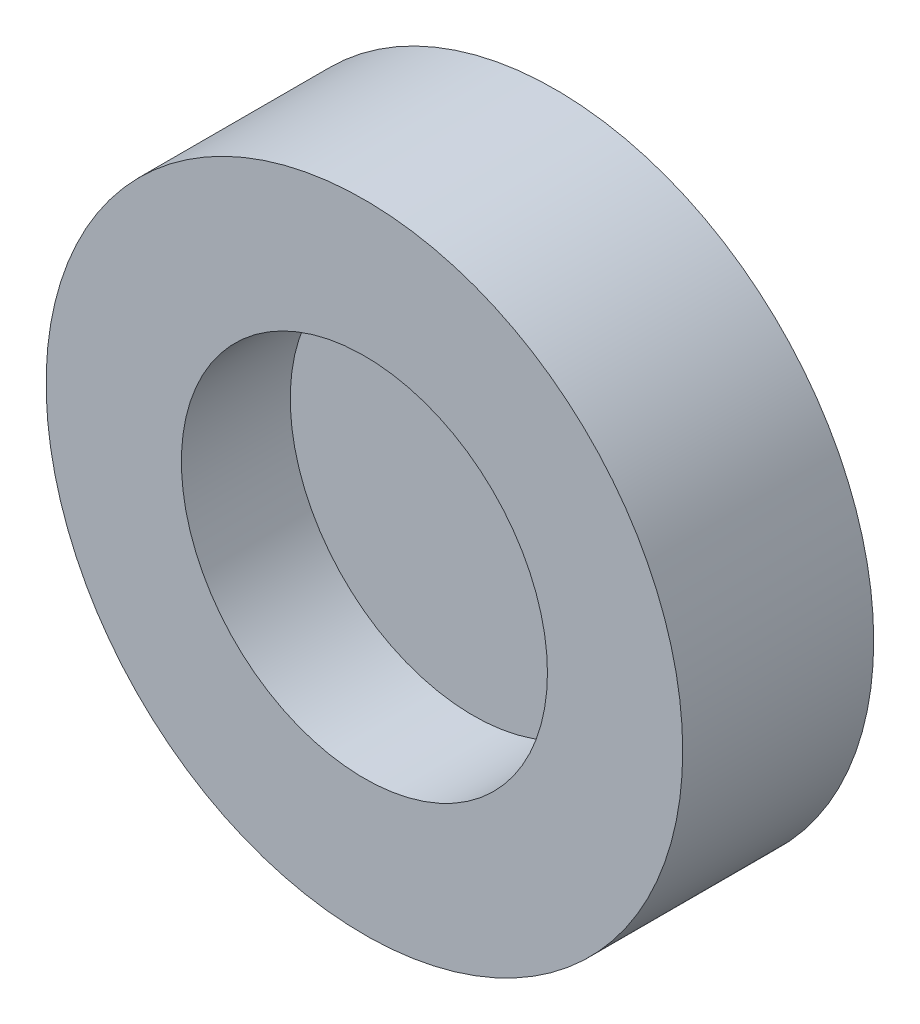
SolidWorks part; units mm, degrees
ref_plane "前视基准面" through (0, 0, 0) normal (0, 0, 1) x (1, 0, 0)
ref_plane "上视基准面" through (0, 0, 0) normal (0, 1, 0) x (1, 0, 0)
ref_plane "右视基准面" through (0, 0, 0) normal (1, 0, 0) x (0, 0, -1)
other "Configuration Table"
sketch "草图1" plane through (0, 0, 0) normal (0, 0, 1) x (1, 0, 0)
  circle A0 centre (-113.7233, 27.9708) radius 10
extrude "凸台-拉伸1" add sketch "草图1" against normal blind 6 from surface at -13.4389
sketch "草图2" plane through (0, 0, -13.4389) normal (0, 0, 1) x (1, 0, 0)
  circle A0 centre (-113.7233, 27.9708) radius 5.75
extrude "切除-拉伸1" cut sketch "草图2" against normal blind 3.42
